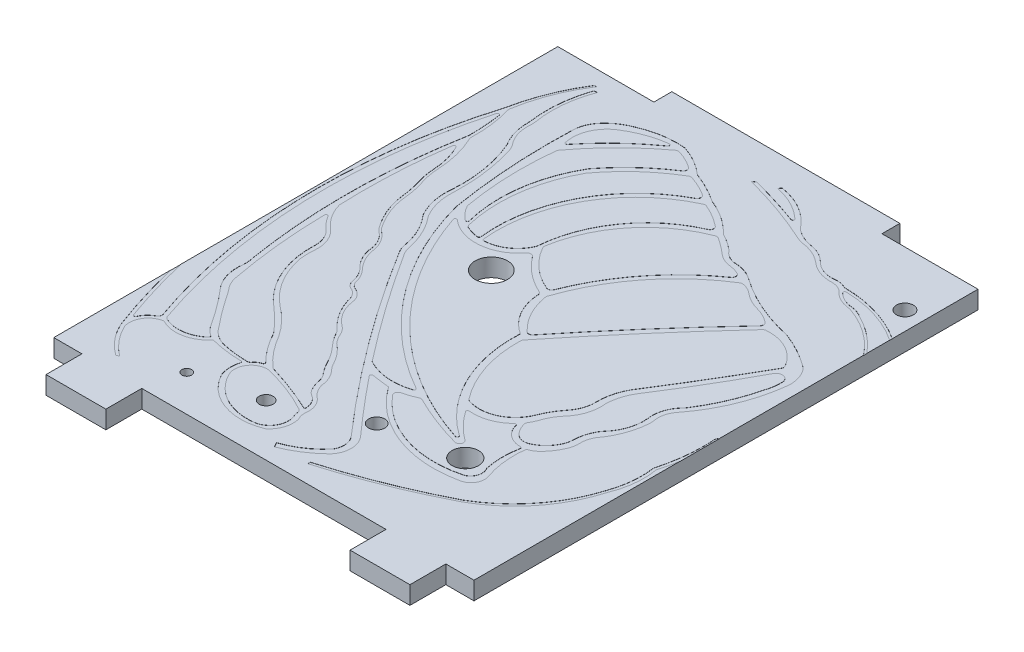
SolidWorks part; units mm, degrees
material "Acrylic (Medium-high impact)"
ref_plane "Front Plane" through (0, 0, 0) normal (0, 0, 1) x (1, 0, 0)
ref_plane "Top Plane" through (0, 0, 0) normal (0, 1, 0) x (1, 0, 0)
ref_plane "Right Plane" through (0, 0, 0) normal (1, 0, 0) x (0, 0, -1)
sketch "스케치1" plane through (0, 0, 0) normal (0, 1, 0) x (1, 0, 0)
  line L1 (-38.1, -42.1) -> (38.1, -42.1)
  line L2 (-38.1, -42.1) -> (-38.1, 42.1)
  line L3 (-38.1, 42.1) -> (38.1, 42.1)
  line L4 (38.1, -42.1) -> (38.1, 42.1)
  line L5 (-38.1, -42.1) -> (38.1, 42.1) construction
  line L6 (-38.1, 42.1) -> (38.1, -42.1) construction
  point P0 (0, 0)
  dimension "D1" = 76.2
  dimension "D2" = 84.2
extrude "보스-돌출1" add sketch "스케치1" along normal blind 3
sketch "스케치3" plane through (0, 3, 0) normal (0, 1, 0) x (1, 0, 0)
  line L0 (-24.7079, 70.3158) -> (119.2921, 70.3158) construction
sketch "스케치6" plane through (0, 3, 0) normal (0, 1, 0) x (1, 0, 0)
  line L0 (-1.2881, -38.6983) -> (-0.857, -39.4898)
  line L1 (-25.689, 38.7484) -> (-25.1527, 38.7484)
  line L3 (3.768, 39.946) -> (4.1283, 40.3797)
  line L4 (39.5502, 23.2374) -> (39.7048, 23.7483)
  line L6 (0.5328, 38.7484) -> (1.1153, 39.1359)
  line L7 (-27.3407, -39.4898) -> (-26.9185, -39.2773)
  line L8 (-26.4332, 39.5465) -> (-26.0436, 39.5465)
  line L9 (4.3402, -38.6983) -> (4.3762, -39.1248)
  line L10 (-40.5146, 0.3969) -> (-40.1027, 0.6378)
  arc A0 (12.9434, -22.3886) -> (3.3207, -2.5756) centre (26.05, -3.7797) cw
  arc A1 (3.3207, -2.5756) -> (-0.8452, 4.5468) centre (8.1245, 5.0137) cw
  arc A2 (-1.2164, 5.0917) -> (-6.8501, 9.6165) centre (4.8389, 18.4007) cw
  arc A3 (-7.8582, 9.6259) -> (-13.9758, 6.834) centre (-13.6013, 14.1117) cw
  arc A5 (12.7186, -22.8378) -> (-18.8456, 8.3775) centre (28.0245, 24.2053) cw
  arc A6 (-18.4372, 8.6494) -> (-13.9758, 6.834) centre (-13.5994, 14.1486) ccw
  arc A7 (4.3682, -3.5712) -> (8.49, -16.3356) centre (24.2129, -4.2107) ccw
  arc A8 (3.6156, -1.7322) -> (0.1175, 4.8106) centre (11.3282, 6.5978) cw
  arc A9 (-1.0911, 6.2399) -> (-7.2574, 11.7591) centre (3.768, 17.873) cw
  arc A10 (-7.9864, 11.42) -> (-13.1978, 7.8223) centre (-13.4357, 13.7401) cw
  arc A11 (-14.2951, 7.8715) -> (-16.3748, 8.4511) centre (-13.5043, 14.7298) cw
  arc A12 (0.1427, 5.113) -> (14.2745, 23.1207) centre (32.5868, -5.799) cw
  arc A13 (-0.255, 6.5945) -> (12.7565, 23.1938) centre (33.8803, -6.7636) cw
  arc A14 (-7.3285, 12.1708) -> (5.4208, 27.8685) centre (12.8165, 8.8357) cw
  arc A15 (-7.9864, 11.42) -> (3.8935, 28.1985) centre (11.8777, 9.9503) cw
  arc A16 (-13.4607, 8.0502) -> (-0.1594, 31.4567) centre (9.6279, 10.4122) cw
  arc A17 (-14.0137, 8.1529) -> (-1.6326, 31.6585) centre (9.3713, 10.8489) cw
  arc A18 (-14.4166, 26.1697) -> (-16.7281, 8.8799) centre (6.7644, 14.5385) ccw
  arc A19 (-17.28, 9.4974) -> (-14.836, 27.0406) centre (5.2347, 15.3026) cw
  arc A20 (-14.4166, 26.1697) -> (-5.4519, 34.2818) centre (10.2299, 7.9422) cw
  arc A21 (-14.836, 27.0406) -> (-6.7312, 34.5245) centre (11.579, 6.5646) cw
  arc A22 (-17.6796, 9.2317) -> (-19.5804, 11.4523) centre (-13.5043, 14.7298) cw
  arc A23 (4.5417, -1.6643) -> (22.1767, 18.5918) centre (274.6921, -219.0535) cw
  arc A24 (4.5069, -3.195) -> (22.93, 18.2342) centre (315.1938, -251.6636) cw
  arc A25 (8.7893, -16.5493) -> (16.3878, -12.9847) centre (10.732, -10.8094) ccw
  arc A26 (16.3878, -12.9847) -> (18.2954, -9.7039) centre (27.5372, -17.2728) cw
  arc A27 (18.2954, -9.7039) -> (19.5243, -6.1207) centre (14.089, -6.259) ccw
  arc A28 (19.5243, -6.1207) -> (21.2018, -0.5978) centre (28.6871, -5.8876) cw
  arc A29 (21.2018, -0.5978) -> (30.102, 14.2353) centre (-298.0973, 201.0752) ccw
  arc A30 (10.2358, -18.0181) -> (15.7855, -16.06) centre (10.9355, -11.1577) ccw
  arc A31 (17.4769, -13.3407) -> (18.9566, -10.7765) centre (24.4996, -15.6843) cw
  arc A32 (18.9566, -10.7765) -> (20.5681, -5.5862) centre (14.0076, -6.3946) ccw
  arc A33 (20.5681, -5.5862) -> (21.8757, -1.3213) centre (28.7329, -5.7565) cw
  arc A34 (21.8757, -1.3213) -> (30.2744, 12.9288) centre (-145.3414, 106.8346) ccw
  arc A35 (30.2744, 12.9288) -> (32.1848, 12.537) centre (31.1393, 12.2926) cw
  arc A36 (32.1848, 12.537) -> (31.8141, 9.6774) centre (25.0627, 12.0064) cw
  arc A37 (31.8141, 9.6774) -> (27.9962, 0.7568) centre (3.465, 16.5333) cw
  arc A38 (27.5735, 0.2143) -> (26.2231, -4.2107) centre (31.4083, -3.3745) ccw
  arc A39 (26.2231, -4.2107) -> (24.4249, -9.6647) centre (19.0762, -4.8778) cw
  arc A40 (23.917, -10.385) -> (23.0837, -13.5228) centre (29.9503, -13.6669) ccw
  arc A41 (22.6777, -15.1561) -> (19.9698, -17.7226) centre (17.762, -12.6815) cw
  arc A42 (17.9418, -17.4031) -> (16.7077, -15.2624) centre (20.5278, -14.4862) cw
  arc A43 (-19.6469, 11.6436) -> (-20.1522, 26.8696) centre (33.6535, 21.0338) cw
  arc A44 (-20.0312, 27.1791) -> (-10.2869, 36.9289) centre (17.6611, -0.7475) cw
  arc A45 (-11.5516, 36.8936) -> (-20.1448, 28.7742) centre (13.1924, 2.0989) ccw
  arc A46 (-20.4541, 10.525) -> (-21.7816, 31.2493) centre (81.1736, 27.4395) cw
  arc A47 (-20.4541, 10.525) -> (2.5213, -19.1816) centre (26.323, 22.965) ccw
  arc A48 (-20.4631, 34.5583) -> (-16.9747, 36.9236) centre (-14.102, 28.9316) cw
  arc A49 (-20.5906, 28.876) -> (-18.082, 35.0413) centre (-14.9483, 30.1731) cw
  arc A50 (-18.082, 35.0413) -> (-11.7308, 37.3526) centre (-9.8087, 22.189) cw
  arc A51 (-16.9747, 36.9236) -> (-9.861, 38.0734) centre (-11.1979, 23.7644) cw
  arc A52 (-9.7221, 37.0259) -> (-6.7206, 35.5798) centre (-12.9759, 26.4343) cw
  arc A53 (-4.9288, 34.3394) -> (-1.5877, 32.7551) centre (-9.5421, 20.2955) cw
  arc A54 (0.3536, 31.4667) -> (4.0368, 29.2752) centre (-5.5661, 17.3267) cw
  arc A55 (5.994, 27.8109) -> (8.6371, 25.8175) centre (-5.9291, 9.2523) cw
  arc A56 (8.6371, 25.8175) -> (11.0513, 24.7435) centre (11.5637, 29.1457) ccw
  arc A57 (11.0513, 24.7435) -> (12.6588, 24.2883) centre (10.4455, 19.5389) cw
  arc A58 (-9.861, 38.0734) -> (-4.8988, 35.2204) centre (-14.1168, 24.9294) cw
  arc A59 (-4.8988, 35.2204) -> (0.1858, 32.6084) centre (-13.5619, 12.1013) cw
  arc A60 (0.1858, 32.6084) -> (5.8798, 28.7913) centre (-5.5603, 17.8817) cw
  arc A61 (5.8798, 28.7913) -> (8.3777, 27.1696) centre (-0.1617, 16.7509) cw
  arc A62 (8.8299, 26.7317) -> (10.7324, 25.5908) centre (11.5508, 29.1123) ccw
  arc A63 (10.7324, 25.5908) -> (14.4833, 24.4131) centre (10.8797, 19.4983) cw
  arc A64 (14.4833, 24.4131) -> (25.731, 19.5147) centre (32.0025, 49.2783) ccw
  arc A65 (25.731, 19.5147) -> (31.8658, 16.1393) centre (16.6712, -4.2146) cw
  arc A66 (31.8658, 16.1393) -> (33.1687, 12.2926) centre (28.0855, 12.715) cw
  arc A67 (33.1687, 12.2926) -> (27.7804, -0.884) centre (7.1895, 15.2261) cw
  arc A68 (14.6991, 23.2136) -> (16.5044, 22.4028) centre (14.2341, 19.7627) cw
  arc A69 (16.5044, 22.4028) -> (19.5243, 20.8207) centre (21.4293, 28.1299) ccw
  arc A70 (19.5243, 20.8207) -> (22.1112, 19.5226) centre (17.7744, 14.1064) cw
  arc A71 (23.3428, 18.4361) -> (30.1033, 14.8612) centre (23.9411, 11.3876) cw
  arc A72 (16.212, -16.1852) -> (19.6512, -18.9009) centre (19.602, -15.4277) ccw
  arc A73 (21.8757, -18.0537) -> (23.8651, -15.1058) centre (15.9671, -11.9209) ccw
  arc A74 (24.1357, -13.4688) -> (24.964, -10.8746) centre (27.9468, -13.2563) cw
  arc A75 (25.2054, -10.5358) -> (27.0909, -4.8134) centre (14.7668, -3.9245) ccw
  arc A76 (27.0408, -3.8659) -> (27.7804, -0.884) centre (30.7423, -3.2013) cw
  arc A77 (19.9698, -17.7226) -> (17.9418, -17.4031) centre (19.2056, -15.9777) cw
  arc A78 (16.7908, -14.8005) -> (17.4769, -13.3407) centre (10.9355, -11.1577) ccw
  arc A79 (20.5278, -18.7756) -> (21.2018, -25.6362) centre (36.2904, -20.6903) ccw
  arc A80 (21.2018, -25.6362) -> (19.602, -28.8648) centre (19.1386, -26.6244) cw
  arc A81 (19.602, -28.8648) -> (0.0674, -21.3634) centre (15.4904, -10.3858) cw
  arc A82 (10.0022, -18.4169) -> (14.089, -22.5963) centre (24.8701, -7.9662) ccw
  arc A83 (13.5443, -23.7207) -> (14.089, -22.5963) centre (13.7121, -23.1078) ccw
  arc A84 (12.9434, -22.3886) -> (12.7186, -22.8378) centre (12.7972, -22.5963) cw
  arc A85 (19.9043, -19.2028) -> (19.9698, -24.8503) centre (33.7691, -21.866) ccw
  arc A86 (19.9698, -24.8503) -> (19.1386, -27.7136) centre (18.3322, -25.9272) cw
  arc A87 (19.1386, -27.7136) -> (1.5277, -22.1168) centre (14.645, -11.3475) cw
  arc A88 (4.0986, -20.3168) -> (1.8791, -21.0944) centre (-0.357, -11.1553) cw
  arc A89 (-0.1167, -21.2577) -> (-2.9613, -20.8815) centre (2.9935, 13.2034) cw
  arc A90 (2.4761, -19.6439) -> (-5.0336, -18.9768) centre (-0.5059, -10.6105) cw
  arc A91 (4.6605, -20.32) -> (13.5443, -23.7207) centre (26.323, 22.965) ccw
  arc A92 (20.5278, -18.7756) -> (21.8757, -18.0537) centre (19.602, -15.4277) ccw
  arc A93 (-1.2881, -38.6983) -> (4.3402, -34.8888) centre (-5.3361, -26.6553) ccw
  arc A94 (4.3402, -34.8888) -> (3.9125, -31.406) centre (1.7968, -33.4335) ccw
  arc A95 (3.9125, -31.406) -> (-18.6555, -0.7851) centre (176.2855, 119.2624) cw
  arc A96 (-19.1692, 0.5848) -> (-22.0015, 6.4969) centre (-30.8184, -1.3614) ccw
  arc A97 (-22.0015, 6.4969) -> (-23.2874, 12.6141) centre (-13.4167, 11.4952) cw
  arc A98 (-23.2874, 12.6141) -> (-25.1527, 23.6635) centre (-46.8609, 14.3166) ccw
  arc A99 (-25.1527, 23.6635) -> (-26.5793, 28.728) centre (-17.5612, 28.535) cw
  arc A100 (-26.5919, 28.9361) -> (-25.689, 38.7484) centre (-5.6192, 31.9539) cw
  arc A101 (4.8207, -35.8367) -> (-0.857, -39.4898) centre (-7.1195, -23.5177) cw
  arc A102 (4.8207, -35.8367) -> (4.8207, -30.7679) centre (1.9854, -33.3023) ccw
  arc A103 (4.8207, -30.7679) -> (-3.2032, -21.2906) centre (177.0575, 123.1901) cw
  arc A104 (-25.1527, 38.7484) -> (-26.0779, 29.3468) centre (-8.2703, 32.3408) ccw
  arc A105 (-26.0397, 28.3829) -> (-24.7775, 24.227) centre (-20.2384, 27.8751) ccw
  arc A106 (-24.1036, 22.9537) -> (-22.7325, 12.537) centre (-54.5539, 13.6473) cw
  arc A107 (-22.7325, 12.537) -> (-21.44, 6.834) centre (-13.0823, 11.7262) ccw
  arc A108 (-21.44, 6.834) -> (-18.4239, 0.5557) centre (-32.2014, -2.1995) cw
  arc A109 (-5.0336, -18.9768) -> (-17.9032, -0.7411) centre (177.0575, 123.1901) cw
  arc A110 (-17.9032, -0.7411) -> (-18.4239, 0.5557) centre (-14.6878, 1.3028) cw
  arc A111 (-18.6555, -0.7851) -> (-19.1692, 0.5848) centre (-15.4113, 1.2127) cw
  arc A112 (-24.7775, 24.227) -> (-24.1036, 22.9537) centre (-27.7472, 21.8401) cw
  arc A113 (-26.0779, 29.3468) -> (-26.0397, 28.3829) centre (-29.8351, 28.7151) cw
  arc A114 (-20.4631, 34.5583) -> (-21.7816, 31.2493) centre (-16.8124, 31.1865) ccw
  arc A115 (8.3777, 27.1696) -> (8.8299, 26.7317) centre (5.9625, 24.2229) cw
  arc A116 (27.9962, 0.7568) -> (27.5735, 0.2143) centre (24.7917, 2.8177) cw
  arc A117 (27.0909, -4.8134) -> (27.0408, -3.8659) centre (23.2908, -4.5393) ccw
  arc A118 (24.4249, -9.6647) -> (23.917, -10.385) centre (27.2639, -12.2056) ccw
  arc A119 (24.964, -10.8746) -> (25.2054, -10.5358) centre (21.9867, -8.4972) ccw
  arc A120 (23.0837, -13.5228) -> (22.6777, -15.1561) centre (19.2745, -13.4429) cw
  arc A121 (23.8651, -15.1058) -> (24.1357, -13.4688) centre (20.3316, -13.6809) ccw
  arc A122 (-12.5716, -28.8124) -> (-15.1507, -32.7676) centre (-12.6923, -31.5522) ccw
  arc A123 (-15.1507, -32.7676) -> (-6.0039, -37.6057) centre (-7.2253, -28.8494) ccw
  arc A124 (-6.0039, -37.6057) -> (-3.7035, -33.3393) centre (-6.5251, -34.5713) ccw
  arc A125 (-3.9161, -32.5268) -> (-3.7035, -33.3393) centre (-2.1283, -32.4929) ccw
  arc A126 (-4.2482, -31.9806) -> (-12.5716, -28.8124) centre (-20.2219, -61.4282) ccw
  arc A127 (-14.9902, -29.1341) -> (-13.9209, -28.4109) centre (-13.4363, -30.2793) cw
  arc A128 (-13.8042, -27.9863) -> (-17.3628, -23.1078) centre (0.5328, -13.7912) cw
  arc A129 (-17.3628, -23.1078) -> (-21.0747, -19.3467) centre (-42.7911, -44.4913) ccw
  arc A130 (-26.6397, -7.0012) -> (-28.4034, -3.3536) centre (-30.9178, -6.8196) ccw
  arc A131 (-21.0747, -19.3467) -> (-26.6397, -7.0012) centre (-11.5822, -7.6407) cw
  arc A132 (-28.4034, -3.3536) -> (-29.766, -1.6231) centre (-20.8991, 3.9569) cw
  arc A133 (-30.235, -1.762) -> (-28.5609, -18.2547) centre (64.911, -0.4357) ccw
  arc A134 (-28.5609, -18.2547) -> (-27.5575, -20.3868) centre (-23.9101, -17.368) ccw
  arc A135 (-26.7366, -21.4962) -> (-22.9204, -26.6553) centre (22.705, 11.085) ccw
  arc A136 (-22.9204, -26.6553) -> (-19.9583, -28.8648) centre (-18.5521, -23.8893) ccw
  arc A137 (-19.9583, -28.8648) -> (-15.5069, -29.3923) centre (-15.3265, -8.8267) ccw
  arc A138 (-28.3183, -29.9561) -> (-22.2483, -29.0971) centre (-25.9329, -24.9362) ccw
  arc A139 (-28.2945, -30.494) -> (-21.5405, -29.241) centre (-25.6977, -25.6622) ccw
  arc A140 (-21.2857, -29.1604) -> (-16.1191, -29.8324) centre (-15.8798, -7.795) ccw
  arc A141 (-15.8775, -30.1557) -> (-15.7748, -33.3393) centre (-10.8329, -31.5864) ccw
  arc A142 (-15.7748, -33.3393) -> (-4.2103, -37.6057) centre (-7.6957, -29.2468) ccw
  arc A143 (-12.5052, -28.1089) -> (-16.4923, -23.1078) centre (1.6617, -12.7246) cw
  arc A144 (-16.4923, -23.1078) -> (-20.7815, -18.6124) centre (-32.3053, -33.9017) ccw
  arc A145 (-20.7815, -18.6124) -> (-25.9329, -10.1254) centre (-11.7868, -7.3459) cw
  arc A146 (-25.9329, -10.1254) -> (-25.9632, -7.5386) centre (-11.726, -8.6655) cw
  arc A147 (-25.9632, -7.5386) -> (-27.7872, -3.1779) centre (-31.1136, -7.131) ccw
  arc A148 (-27.7872, -3.1779) -> (-30.4331, 0.9613) centre (-22.4784, 3.1311) cw
  arc A149 (-30.4331, 0.9613) -> (-29.5413, 18.9993) centre (68.3729, 5.1174) cw
  arc A150 (-29.0913, 21.2993) -> (-27.4141, 14.4863) centre (-45.606, 13.6209) cw
  arc A151 (-26.755, 11.009) -> (-26.0907, 7.8293) centre (-39.4827, 6.6904) cw
  arc A152 (-20.9795, -3.1719) -> (-23.0722, 0.6378) centre (-26.3322, -3.6325) ccw
  arc A153 (-23.6384, 1.2391) -> (-24.8146, 3.2639) centre (-8.8913, 11.1589) cw
  arc A154 (-20.9795, -3.1719) -> (-19.2496, -6.3886) centre (-14.0588, -1.5236) ccw
  arc A155 (-19.2496, -6.3886) -> (-17.9836, -8.4912) centre (-22.95, -10.0492) cw
  arc A156 (-17.9836, -8.4912) -> (-16.9435, -9.8662) centre (-16.3515, -8.3375) ccw
  arc A157 (-16.9435, -9.8662) -> (-15.3265, -11.9209) centre (-17.8703, -12.2592) cw
  arc A158 (-15.3265, -11.9209) -> (-12.7361, -16.3054) centre (-8.8672, -11.0621) ccw
  arc A159 (-12.7361, -16.3054) -> (-11.5822, -17.8037) centre (-14.7761, -19.07) cw
  arc A160 (-11.5822, -17.8037) -> (-10.5863, -19.3467) centre (-5.979, -15.28) ccw
  arc A161 (-10.5863, -19.3467) -> (-8.0245, -22.383) centre (-16.3163, -26.7798) cw
  arc A162 (-8.0245, -22.383) -> (-7.2659, -23.5177) centre (-3.3826, -20.1006) ccw
  arc A163 (-7.2659, -23.5177) -> (-5.8174, -26.6553) centre (-10.7428, -27.026) cw
  arc A164 (-5.8174, -26.6553) -> (-4.6152, -28.6163) centre (-1.7456, -25.5079) ccw
  arc A165 (-4.6152, -28.6163) -> (-3.1747, -31.8246) centre (-6.6239, -31.4457) cw
  arc A166 (-3.1747, -31.8246) -> (-2.8894, -33.3393) centre (-0.8898, -32.1786) ccw
  arc A167 (-2.8894, -33.3393) -> (-4.2103, -37.6057) centre (-6.7739, -34.4744) cw
  arc A168 (-12.2561, -28.2504) -> (-3.8886, -31.4457) centre (-29.1405, -85.0188) cw
  arc A169 (-3.8886, -31.4457) -> (-5.1493, -28.947) centre (-6.5315, -31.2118) ccw
  arc A170 (-6.0452, -28.0146) -> (-6.6928, -26.1745) centre (-1, -25.2051) cw
  arc A171 (-7.2508, -24.9684) -> (-8.6188, -22.8995) centre (1.1153, -17.95) cw
  arc A172 (-10.5863, -20.0645) -> (-12.1913, -17.8037) centre (-2.4349, -12.5771) cw
  arc A173 (-12.7361, -17.1107) -> (-15.8798, -12.2035) centre (-5.4728, -8.997) cw
  arc A174 (-22.2765, -28.695) -> (-23.8948, -26.9729) centre (-19.4428, -24.4109) cw
  arc A175 (-23.8948, -26.9729) -> (-28.5609, -20.7582) centre (-70.7563, -57.2986) ccw
  arc A176 (-28.5609, -20.7582) -> (-29.8351, -15.6843) centre (-23.0692, -16.6821) cw
  arc A177 (-29.8351, -15.6843) -> (-30.052, -13.6809) centre (-36.5678, -15.3997) ccw
  arc A178 (-30.052, -13.6809) -> (-29.6973, 21.7303) centre (74.1849, 2.9822) cw
  arc A179 (-29.0624, 19.0767) -> (-27.7433, 14.0804) centre (-40.5146, 13.3809) cw
  arc A180 (-27.2151, 11.0871) -> (-26.487, 7.5726) centre (-46.2477, 5.3115) cw
  arc A181 (-25.4399, 3.7808) -> (-23.7983, 0.9428) centre (-10.4032, 10.5848) ccw
  arc A182 (-23.2638, 0.3969) -> (-21.44, -3.1779) centre (-26.014, -3.2589) cw
  arc A183 (-21.44, -3.1779) -> (-19.4428, -6.6196) centre (-15.1079, -1.8038) ccw
  arc A184 (-19.4428, -6.6196) -> (-18.3222, -8.997) centre (-22.8576, -9.682) cw
  arc A185 (-18.3222, -8.997) -> (-17.3628, -10.1657) centre (-16.7546, -8.6883) ccw
  arc A186 (-17.3628, -10.1657) -> (-15.8798, -12.2035) centre (-18.4538, -12.5182) cw
  arc A187 (0.5328, 38.7484) -> (12.7186, 34.4272) centre (-16.9036, -29.7641) cw
  arc A188 (1.1153, 39.1359) -> (9.3712, 36.5736) centre (-22.0035, -49.9377) cw
  arc A189 (9.6294, 36.9997) -> (3.768, 39.946) centre (1.4939, 28.1184) ccw
  arc A190 (4.1283, 40.3797) -> (11.5637, 35.9429) centre (2.3931, 29.023) cw
  arc A191 (11.5637, 35.9429) -> (15.1529, 34.4272) centre (16.029, 41.5092) ccw
  arc A192 (15.1529, 34.4272) -> (17.9418, 32.9199) centre (14.0289, 29.0135) cw
  arc A193 (17.9418, 32.9199) -> (21.9867, 31.5726) centre (21.257, 36.1272) ccw
  arc A194 (12.7186, 34.4272) -> (13.6307, 34.1245) centre (15.6415, 41.71) ccw
  arc A195 (13.6307, 34.1245) -> (17.807, 32.3124) centre (12.8868, 26.6915) cw
  arc A196 (17.807, 32.3124) -> (21.9867, 30.8941) centre (21.6452, 36.7558) ccw
  arc A197 (21.9867, 31.5726) -> (23.674, 31.1865) centre (22.1934, 28.5963) cw
  arc A198 (23.674, 31.1865) -> (39.7048, 23.7483) centre (23.6077, 10.0496) cw
  arc A199 (21.9867, 30.8941) -> (24.2129, 29.7513) centre (21.9407, 28.0647) cw
  arc A200 (24.2129, 29.7513) -> (27.2639, 28.535) centre (27.6235, 33.8716) ccw
  arc A201 (27.2639, 28.535) -> (38.4172, 15.5358) centre (21.8683, 12.6212) cw
  arc A202 (24.3357, 30.2538) -> (26.7061, 29.0135) centre (27.5779, 33.5648) ccw
  arc A203 (26.7061, 29.0135) -> (29.1829, 28.2466) centre (26.5645, 24.1731) cw
  arc A204 (29.1829, 28.2466) -> (38.9018, 15.5358) centre (21.0235, 11.9368) cw
  arc A205 (24.5187, 30.6893) -> (39.5502, 23.2374) centre (24.1057, 10.9699) cw
  arc A206 (-29.6771, 21.9544) -> (-30.0584, 27.2432) centre (-65.9521, 21.9968) ccw
  arc A207 (-28.6455, -29.5911) -> (-30.5547, 27.2736) centre (61.9837, 1.9161) cw
  arc A208 (-29.3389, -29.6069) -> (-30.6795, 28.8367) centre (59.3228, 1.664) cw
  arc A209 (-29.209, 21.8756) -> (-30.052, 28.5667) centre (-50.6929, 22.5675) ccw
  arc A210 (-30.0853, 29.1297) -> (-26.0436, 39.5465) centre (-3.0329, 24.6261) cw
  arc A211 (-30.6795, 28.8367) -> (-26.4332, 39.5465) centre (0.2251, 22.7802) cw
  arc A212 (-29.6426, -30.3804) -> (-31.2723, -32.1366) centre (-27.9698, -33.5669) ccw
  arc A213 (-28.2945, -30.494) -> (-30.8184, -34.5713) centre (-27.7917, -33.6251) ccw
  arc A214 (-30.8184, -34.5713) -> (-26.9185, -39.2773) centre (-19.3105, -29.0035) ccw
  arc A215 (-31.4257, -34.5713) -> (-27.3407, -39.4898) centre (-20.3382, -29.5183) ccw
  arc A216 (-8.6188, -22.8995) -> (-10.5863, -20.0645) centre (-19.9394, -28.6557) ccw
  arc A217 (-26.487, 7.5726) -> (-25.4399, 3.7808) centre (-13.8693, 9.0164) ccw
  arc A218 (-26.0907, 7.8293) -> (-24.8146, 3.2639) centre (-13.4363, 8.9054) ccw
  arc A219 (-27.7433, 14.0804) -> (-27.2151, 11.0871) centre (-15.0623, 14.7749) ccw
  arc A220 (-27.4141, 14.4863) -> (-26.755, 11.009) centre (-14.7285, 15.0897) ccw
  arc A221 (-23.0722, 0.6378) -> (-23.6384, 1.2391) centre (-21.5309, 2.6568) cw
  arc A222 (-23.7983, 0.9428) -> (-23.2638, 0.3969) centre (-21.7369, 2.4267) ccw
  arc A223 (-12.1913, -17.8037) -> (-12.7361, -17.1107) centre (-14.4303, -19.0031) ccw
  arc A224 (-5.1493, -28.947) -> (-6.0452, -28.0146) centre (-3.8261, -26.7789) cw
  arc A225 (-6.6928, -26.1745) -> (-7.2508, -24.9684) centre (-9.1968, -26.6008) ccw
  arc A226 (-27.5575, -20.3868) -> (-26.7366, -21.4962) centre (-37.3411, -28.4844) cw
  arc A227 (4.3402, -38.6983) -> (22.6253, -31.406) centre (-25.0789, 61.6385) ccw
  arc A228 (22.6253, -31.406) -> (33.1687, -18.0537) centre (10.8833, -11.2953) ccw
  arc A229 (33.1687, -18.0537) -> (33.8803, -10.8746) centre (19.012, -13.0255) ccw
  arc A230 (33.8803, -10.8746) -> (34.84, -1.5236) centre (7.5497, -3.4477) ccw
  arc A231 (34.84, -1.5236) -> (38.4172, 15.5358) centre (9.6748, 12.6581) ccw
  arc A232 (38.9018, 15.5358) -> (35.3559, -1.5236) centre (9.1648, 12.8186) cw
  arc A233 (35.3559, -1.5236) -> (34.3578, -10.8746) centre (10.4186, -3.5907) cw
  arc A234 (34.3578, -10.8746) -> (33.5546, -18.2547) centre (21.2591, -13.1826) cw
  arc A235 (33.5546, -18.2547) -> (22.6777, -31.8246) centre (11.8351, -11.9898) cw
  arc A236 (22.6777, -31.8246) -> (4.3762, -39.1248) centre (-24.6851, 60.3234) cw
  arc A237 (-31.7441, -32.1223) -> (-35.9163, -16.8394) centre (59.7779, 1.0739) cw
  arc A238 (-36.2097, -17.4031) -> (-31.4257, -34.5713) centre (62.437, 0.8349) ccw
  arc A239 (-35.9163, -16.8394) -> (-40.1027, 0.6378) centre (2335.3219, 560.3944) cw
  arc A240 (-40.5146, 0.3969) -> (-36.2097, -17.4031) centre (-1575.3658, -380.226) cw
  arc A241 (-20.1522, 26.8696) -> (-20.0312, 27.1791) centre (-19.5209, 26.8011) cw
  arc A242 (-1.6326, 31.6585) -> (-1.5877, 32.7551) centre (-1.9294, 32.2199) ccw
  arc A243 (-6.7312, 34.5245) -> (-6.7206, 35.5798) centre (-7.0791, 35.0557) ccw
  arc A244 (-10.2869, 36.9289) -> (-9.7221, 37.0259) centre (-9.9086, 36.4189) cw
  arc A245 (-5.4519, 34.2818) -> (-4.9288, 34.3394) centre (-5.127, 33.7361) cw
  arc A246 (-0.1594, 31.4567) -> (0.3536, 31.4667) centre (0.1083, 30.8809) cw
  arc A247 (3.8935, 28.1985) -> (4.0368, 29.2752) centre (3.639, 28.7802) ccw
  arc A248 (5.4208, 27.8685) -> (5.994, 27.8109) centre (5.6507, 27.2766) cw
  arc A249 (12.7565, 23.1938) -> (12.6588, 24.2883) centre (12.3906, 23.7127) ccw
  arc A250 (14.2745, 23.1207) -> (14.6991, 23.2136) centre (14.6143, 22.5843) cw
  arc A251 (22.1767, 18.5918) -> (22.1112, 19.5226) centre (21.7143, 19.027) ccw
  arc A252 (22.93, 18.2342) -> (23.3428, 18.4361) centre (23.3965, 17.8034) cw
  arc A253 (30.102, 14.2353) -> (30.1033, 14.8612) centre (29.5502, 14.5494) ccw
  arc A254 (-29.3389, -29.6069) -> (-29.6426, -30.3804) centre (-29.9377, -29.8182) cw
  arc A255 (-28.3183, -29.9561) -> (-28.6455, -29.5911) centre (-28.0458, -29.3826) cw
  arc A256 (-14.9902, -29.1341) -> (-15.5069, -29.3923) centre (-15.5013, -28.7574) cw
  arc A257 (-12.5052, -28.1089) -> (-12.2561, -28.2504) centre (-12.075, -27.6418) ccw
  arc A258 (-3.9161, -32.5268) -> (-4.2482, -31.9806) centre (-4.551, -32.5388) ccw
  arc A259 (1.5277, -22.1168) -> (1.8791, -21.0944) centre (2.0184, -21.7139) cw
  arc A260 (4.0986, -20.3168) -> (4.6605, -20.32) centre (4.3763, -20.8878) cw
  arc A261 (16.7077, -15.2624) -> (16.7908, -14.8005) centre (17.33, -15.136) cw
  arc A262 (8.49, -16.3356) -> (8.7893, -16.5493) centre (8.9928, -15.9478) ccw
  arc A263 (4.5069, -3.195) -> (4.3682, -3.5712) centre (5.0028, -3.5916) ccw
  arc A264 (-19.6469, 11.6436) -> (-19.5804, 11.4523) centre (-19.0216, 11.7537) ccw
  arc A265 (-16.7281, 8.8799) -> (-16.3748, 8.4511) centre (-16.1108, 9.0286) ccw
  arc A266 (-7.3285, 12.1708) -> (-7.2574, 11.7591) centre (-6.7021, 12.067) ccw
  arc A267 (-6.8501, 9.6165) -> (-7.8582, 9.6259) centre (-7.3578, 9.235) ccw
  arc A268 (-0.8452, 4.5468) -> (-1.2164, 5.0917) centre (-1.4793, 4.5137) ccw
  arc A269 (-0.255, 6.5945) -> (-1.0911, 6.2399) centre (-0.8463, 6.8259) cw
  arc A270 (0.1427, 5.113) -> (0.1175, 4.8106) centre (0.7446, 4.9106) ccw
  arc A271 (4.5417, -1.6643) -> (3.6156, -1.7322) centre (4.047, -1.2662) cw
  arc A272 (-29.766, -1.6231) -> (-30.235, -1.762) centre (-29.981, -1.7584) ccw
  arc A273 (-30.5547, 27.2736) -> (-30.0584, 27.2432) centre (-30.3098, 27.2065) cw
  arc A274 (-29.5413, 18.9993) -> (-29.0624, 19.0767) centre (-29.2899, 18.9636) cw
  arc A275 (-20.1448, 28.7742) -> (-20.5906, 28.876) centre (-20.3431, 28.9329) cw
  arc A276 (-11.5516, 36.8936) -> (-11.7308, 37.3526) centre (-11.6988, 37.1006) ccw
  arc A277 (16.212, -16.1852) -> (15.7855, -16.06) centre (15.9641, -16.2406) ccw
  arc A278 (19.9043, -19.2028) -> (19.6512, -18.9009) centre (19.6548, -19.1549) ccw
  arc A279 (-31.2723, -32.1366) -> (-31.7441, -32.1223) centre (-31.5053, -32.0357) cw
  arc A280 (-16.1191, -29.8324) -> (-15.8775, -30.1557) centre (-16.1219, -30.0864) cw
  arc A281 (-21.5405, -29.241) -> (-21.2857, -29.1604) centre (-21.348, -29.4067) cw
  arc A282 (-22.2483, -29.0971) -> (-22.2765, -28.695) centre (-22.4167, -28.9069) ccw
  arc A283 (-13.9209, -28.4109) -> (-13.8042, -27.9863) centre (-13.9847, -28.165) ccw
  arc A284 (2.4761, -19.6439) -> (2.5213, -19.1816) centre (2.3964, -19.4027) ccw
  arc A285 (0.0674, -21.3634) -> (-0.1167, -21.2577) centre (-0.1395, -21.5107) ccw
  arc A286 (-2.9613, -20.8815) -> (-3.2032, -21.2906) centre (-3.005, -21.1318) ccw
  arc A287 (10.2358, -18.0181) -> (10.0022, -18.4169) centre (10.21, -18.2708) ccw
  arc A288 (-18.4372, 8.6494) -> (-18.8456, 8.3775) centre (-18.605, 8.4587) ccw
  arc A289 (-17.28, 9.4974) -> (-17.6796, 9.2317) centre (-17.526, 9.434) cw
  arc A290 (-13.4607, 8.0502) -> (-13.1978, 7.8223) centre (-13.208, 8.0761) ccw
  arc A291 (-14.0137, 8.1529) -> (-14.2951, 7.8715) centre (-14.266, 8.1238) cw
  arc A292 (-26.5793, 28.728) -> (-26.5919, 28.9361) centre (-27.849, 28.7552) ccw
  arc A293 (-30.052, 28.5667) -> (-30.0853, 29.1297) centre (-28.8325, 28.9212) cw
  arc A294 (-29.209, 21.8756) -> (-29.0913, 21.2993) centre (-27.9397, 21.8347) ccw
  arc A295 (-29.6771, 21.9544) -> (-29.6973, 21.7303) centre (-30.9471, 21.9559) cw
  arc A296 (24.3357, 30.2538) -> (24.5187, 30.6893) centre (24.5134, 30.4353) cw
  arc A297 (9.3712, 36.5736) -> (9.6294, 36.9997) centre (9.4578, 36.8124) ccw
  point P524 (4.3762, -20.1765)
  point P527 (16.6633, -14.9978)
  point P584 (-17.0989, 8.8357)
  point P587 (-13.4357, 7.8175)
  dimension "D1" = 1.905
  dimension "D2" = 0.254
  dimension "D3" = 3.81
  dimension "D4" = 12.7
  dimension "D5" = 2.54
  dimension "D6" = 12.7
  dimension "D7" = 0.635
  dimension "D8" = 0.254
  dimension "D9" = 1.27
  dimension "D10" = 0.254
extrude "컷-돌출1" cut sketch "스케치6" against normal blind 0.025
sketch "스케치7" plane through (0, 3, 0) normal (0, 1, 0) x (1, 0, 0)
  circle A0 centre (-8.303, -33.4228) radius 1.1645
  circle A1 centre (4.3016, -27.5617) radius 1.3403
  circle A2 centre (16.7078, -25.1594) radius 2.1986
  circle A3 centre (-18.9627, -36.0221) radius 0.8053
  circle A6 centre (-8.303, 4.2011) radius 2.7037
  circle A7 centre (32.0051, 32.9922) radius 1.4172
extrude "컷-돌출2" cut sketch "스케치7" against normal up to surface (3 mm away) up to face at (0, 0, 0)
sketch "스케치8" plane through (0, 3, 0) normal (0, 1, 0) x (1, 0, 0)
  line L0 (-38.1, -42.1) -> (38.1, -42.1) construction
  line L1 (-38.1, 42.1) -> (-35.1, 42.1)
  line L2 (-38.1, 42.1) -> (-38.1, -42.1)
  line L3 (-38.1, -42.1) -> (-35.1, -42.1)
  line L4 (-35.1, 42.1) -> (-35.1, -42.1)
  line L5 (-38.1, 42.1) -> (-35.1, -42.1) construction
  line L6 (-38.1, -42.1) -> (-35.1, 42.1) construction
  line L7 (38.1, 42.1) -> (-38.1, 42.1) construction
  line L8 (38.1, -42.1) -> (35.1, -42.1)
  line L9 (38.1, -42.1) -> (38.1, 42.1)
  line L10 (38.1, 42.1) -> (35.1, 42.1)
  line L11 (35.1, -42.1) -> (35.1, 42.1)
  line L12 (38.1, -42.1) -> (35.1, 42.1) construction
  line L13 (38.1, 42.1) -> (35.1, -42.1) construction
  point P4 (-36.6, 0)
  point P12 (36.6, 0)
  dimension "D1" = 3
  dimension "D2" = 3
extrude "컷-돌출3" cut sketch "스케치8" against normal up to surface (3 mm away) up to face at (32.0051, 0, -34.4094)
sketch "스케치9" plane through (0, 3, 0) normal (0, 1, 0) x (1, 0, 0)
  line L0 (-38.1, -42.1) -> (38.1, -42.1) construction
  line L1 (-35.1, 42.1) -> (35.1, 42.1) construction
  line L2 (0, 42.1) -> (0, -42.1) construction
  line L3 (-35.1, -42.1) -> (35.1, -42.1) construction
  line L4 (30.4, -42.1) -> (20.4, -42.1)
  line L5 (-30.4, -45.1) -> (-20.4, -45.1)
  line L6 (-30.4, -45.1) -> (-30.4, -42.1)
  line L7 (-30.4, -42.1) -> (-20.4, -42.1)
  line L8 (-20.4, -45.1) -> (-20.4, -42.1)
  line L9 (-30.4, -45.1) -> (-20.4, -42.1) construction
  line L10 (-30.4, -42.1) -> (-20.4, -45.1) construction
  line L11 (20.4, -45.1) -> (20.4, -42.1)
  line L12 (30.4, -45.1) -> (20.4, -45.1)
  line L13 (30.4, -45.1) -> (30.4, -42.1)
  line L15 (-12.7, 39.1) -> (12.7, 39.1) construction
  line L16 (-12.7, 39.1) -> (-12.7, 42.1) construction
  line L17 (-12.7, 42.1) -> (12.7, 42.1) construction
  line L18 (12.7, 39.1) -> (12.7, 42.1) construction
  line L19 (-12.7, 39.1) -> (12.7, 42.1) construction
  line L20 (-12.7, 42.1) -> (12.7, 39.1) construction
  point P2 (0, -42.1)
  point P7 (0, 42.1)
  point P12 (-25.4, -43.6)
  point P21 (0, 40.6)
  dimension "D1" = 76.2
  dimension "D2" = 25.4
  dimension "D3" = 10
  dimension "D4" = 3
  dimension "D5" = 25.4
  dimension "D6" = 3
extrude "보스-돌출2" add sketch "스케치9" against normal up to surface (3 mm away) up to face at (0, 0, 0)
sketch "스케치11" plane through (0, 0, 45.1) normal (0, 0, 1) x (1, 0, 0)
  line L0 (20.4, 3) -> (20.4, 0) construction
  line L1 (20.4, 0) -> (30.4, 0) construction
  line L2 (30.4, 0) -> (30.4, 3) construction
  line L3 (30.4, 3) -> (20.4, 3) construction
  line L4 (-30.4, 3) -> (-30.4, 0) construction
  line L5 (-30.4, 0) -> (-20.4, 0) construction
  line L6 (-20.4, 0) -> (-20.4, 3) construction
  line L7 (-20.4, 3) -> (-30.4, 3) construction
  line L8 (20.4, 3) -> (20.4, 0)
  line L9 (20.4, 0) -> (30.4, 0)
  line L10 (30.4, 0) -> (30.4, 3)
  line L11 (30.4, 3) -> (20.4, 3)
  line L12 (-30.4, 3) -> (-30.4, 0)
  line L13 (-30.4, 0) -> (-20.4, 0)
  line L14 (-20.4, 0) -> (-20.4, 3)
  line L15 (-20.4, 3) -> (-30.4, 3)
extrude "보스-돌출3" add sketch "스케치11" along normal blind 3
sketch "스케치12" plane through (0, 3, 0) normal (0, 1, 0) x (1, 0, 0)
  line L0 (35.1, 42.1) -> (-35.1, 42.1) construction
  line L1 (-19.05, 45.1) -> (19.05, 45.1)
  line L2 (-19.05, 45.1) -> (-19.05, 42.1)
  line L3 (-19.05, 42.1) -> (19.05, 42.1)
  line L4 (19.05, 45.1) -> (19.05, 42.1)
  line L5 (-19.05, 45.1) -> (19.05, 42.1) construction
  line L6 (-19.05, 42.1) -> (19.05, 45.1) construction
  line L7 (0, 0) -> (0, 43.6) construction
  point P0 (0, 43.6)
  dimension "D1" = 3
  dimension "D2" = 38.1
extrude "보스-돌출4" add sketch "스케치12" against normal up to surface (3 mm away) up to face at (0, 0, 30.0667)
